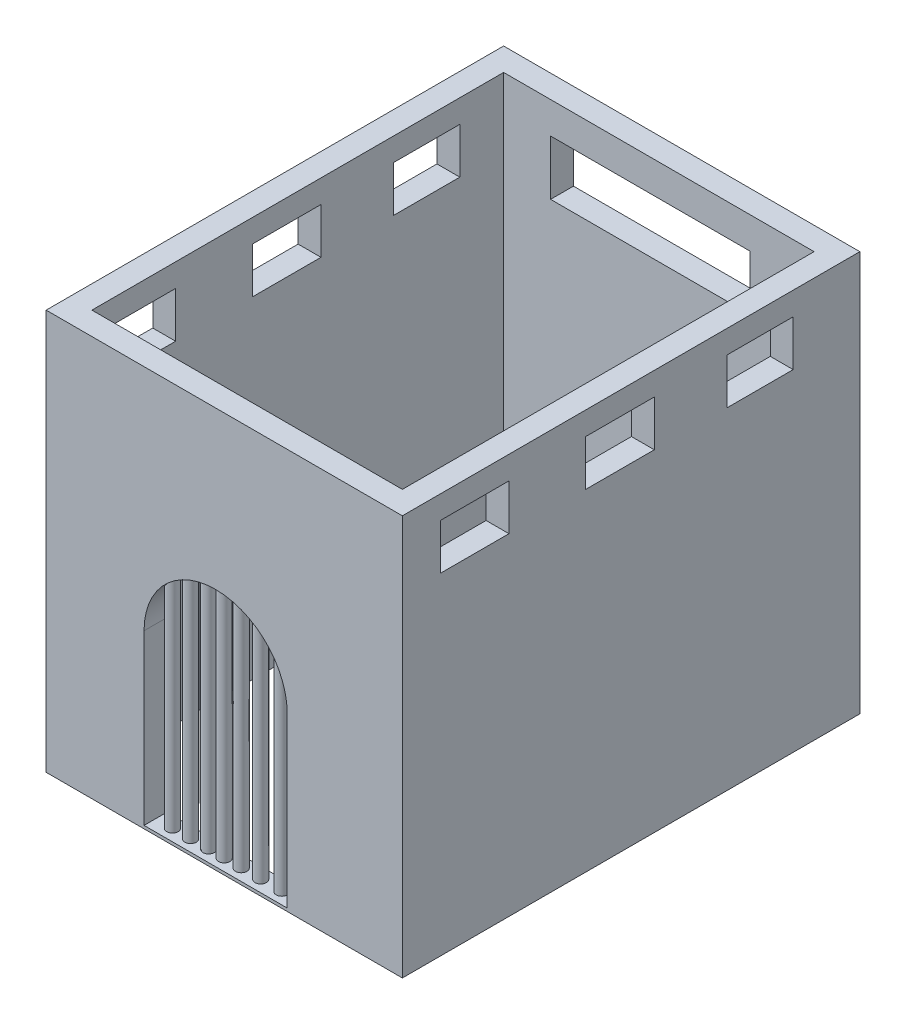
SolidWorks part; units mm, degrees
ref_plane "Front Plane" through (0, 0, 0) normal (0, 0, 1) x (1, 0, 0)
ref_plane "Top Plane" through (0, 0, 0) normal (0, 1, 0) x (1, 0, 0)
ref_plane "Right Plane" through (0, 0, 0) normal (1, 0, 0) x (0, 0, -1)
sketch "Sketch2" plane through (0, 0, 0) normal (0, 1, 0) x (1, 0, 0)
  line L0 (14327.9287, 18969.4269) -> (-12818.2325, 18969.4269)
  line L1 (16327.9287, 20969.4269) -> (-14818.2325, 20969.4269)
  line L2 (16327.9287, 20969.4269) -> (16327.9287, -19030.5731)
  line L3 (16327.9287, -19030.5731) -> (-14818.2325, -19030.5731)
  line L4 (-14818.2325, 20969.4269) -> (-14818.2325, -19030.5731)
  line L7 (-12818.2325, 18969.4269) -> (-12818.2325, -17030.5731)
  line L8 (14327.9287, -17030.5731) -> (-12818.2325, -17030.5731)
  line L9 (14327.9287, 18969.4269) -> (14327.9287, -17030.5731)
  point P0 (0, 0)
  dimension "D1" = 2000
extrude "Boss-Extrude1" add sketch "Sketch2" along normal blind 35000 contours L0 L7 L8 L9 | L2 L1 L4 L3
sketch "Sketch3" plane through (0, 0, 19030.5731) normal (0, 0, 1) x (1, 0, 0)
  line L1 (-6258.4161, 15000) -> (-6258.4161, 0)
  line L2 (16327.9287, 0) -> (-14818.2325, 0) construction
  line L3 (-6258.4161, 0) -> (6258.4161, 0)
  line L4 (6258.4161, 0) -> (6258.4161, 15000)
  arc A0 (6258.4161, 15000) -> (-6258.4161, 15000) centre (0, 15000) ccw
extrude "Cut-Extrude1" cut sketch "Sketch3" against normal blind 25931
sketch "Sketch4" plane through (0, 0, 0) normal (0, -1, 0) x (1, 0, 0)
  line L1 (-6258.4161, 17030.5731) -> (6258.4161, 17030.5731)
  line L2 (-6258.4161, 17030.5731) -> (-6258.4161, 19030.5731)
  line L3 (-6258.4161, 19030.5731) -> (6258.4161, 19030.5731)
  line L4 (6258.4161, 17030.5731) -> (6258.4161, 19030.5731)
extrude "Boss-Extrude2" add sketch "Sketch4" against normal blind 262
sketch "Sketch5" plane through (0, 262, 0) normal (0, 1, 0) x (1, 0, 0)
  circle A1 centre (-1622.7291, -18016.6139) radius 500
  circle A2 centre (-3195.7955, -18016.6139) radius 500
  circle A3 centre (-4792.0999, -18016.6139) radius 500
  circle A4 centre (-263.6539, -18016.6139) radius 500
  circle A5 centre (1225.2306, -18016.6139) radius 500
  circle A6 centre (2925.2771, -18016.6139) radius 500
  circle A7 centre (4780.9571, -18016.6139) radius 500
extrude "Boss-Extrude3" add sketch "Sketch5" along normal blind 23635
sketch "Sketch6" plane through (16327.9287, 0, 0) normal (1, 0, 0) x (0, 0, -1)
  line L1 (3000, 32983.7175) -> (-3000, 32983.7175)
  line L2 (3000, 32983.7175) -> (3000, 28983.7175)
  line L3 (3000, 28983.7175) -> (-3000, 28983.7175)
  line L4 (-3000, 32983.7175) -> (-3000, 28983.7175)
  line L5 (3000, 32983.7175) -> (-3000, 28983.7175) construction
  line L6 (3000, 28983.7175) -> (-3000, 32983.7175) construction
  line L7 (-9709.9815, 32983.7175) -> (-15709.9815, 32983.7175)
  line L8 (-9709.9815, 32983.7175) -> (-9709.9815, 28983.7175)
  line L9 (-9709.9815, 28983.7175) -> (-15709.9815, 28983.7175)
  line L10 (-15709.9815, 32983.7175) -> (-15709.9815, 28983.7175)
  line L11 (-9709.9815, 32983.7175) -> (-15709.9815, 28983.7175) construction
  line L12 (-9709.9815, 28983.7175) -> (-15709.9815, 32983.7175) construction
  line L13 (15140.8512, 32983.7175) -> (9360.8512, 32983.7175)
  line L14 (15140.8512, 32983.7175) -> (15140.8512, 28983.7173)
  line L15 (15140.8512, 28983.7173) -> (9360.8512, 28983.7173)
  line L16 (9360.8512, 32983.7175) -> (9360.8512, 28983.7173)
  line L17 (15140.8512, 32983.7175) -> (9360.8512, 28983.7173) construction
  line L18 (15140.8512, 28983.7173) -> (9360.8512, 32983.7175) construction
  point P0 (0, 30983.7175)
  point P5 (-12709.9815, 30983.7175)
  point P10 (12250.8512, 30983.7174)
extrude "Cut-Extrude2" cut sketch "Sketch6" against normal blind 37179
sketch "Sketch7" plane through (0, 0, -20969.4269) normal (0, 0, -1) x (-1, 0, 0)
  line L1 (8711.7948, 32237.2091) -> (-8711.7948, 32237.2091)
  line L2 (8711.7948, 32237.2091) -> (8711.7948, 27441.2413)
  line L3 (8711.7948, 27441.2413) -> (-8711.7948, 27441.2413)
  line L4 (-8711.7948, 32237.2091) -> (-8711.7948, 27441.2413)
  line L5 (8711.7948, 32237.2091) -> (-8711.7948, 27441.2413) construction
  line L6 (8711.7948, 27441.2413) -> (-8711.7948, 32237.2091) construction
  point P0 (0, 29839.2252)
extrude "Cut-Extrude3" cut sketch "Sketch7" against normal blind 22021
